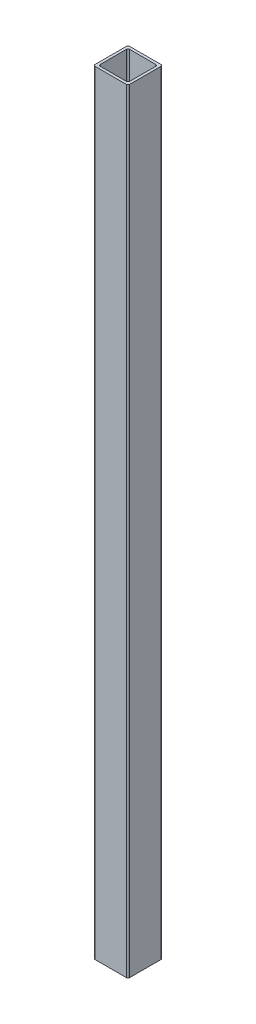
SolidWorks part; units mm, degrees
material "Hexcel AS4C (3000 Filaments)"
ref_plane "Front Plane" through (0, 0, 0) normal (0, 0, 1) x (1, 0, 0)
ref_plane "Top Plane" through (0, 0, 0) normal (0, 1, 0) x (1, 0, 0)
ref_plane "Right Plane" through (0, 0, 0) normal (1, 0, 0) x (0, 0, -1)
sketch "Sketch1" plane through (0, 0, 0) normal (0, 1, 0) x (1, 0, 0)
  line L1 (-9, -10) -> (9, -10)
  line L2 (-10, -9) -> (-10, 9)
  line L3 (-9, 10) -> (9, 10)
  line L4 (10, -9) -> (10, 9)
  line L5 (-10, -10) -> (10, 10) construction
  line L6 (-10, 10) -> (10, -10) construction
  line L7 (-7.5, -8.5) -> (7.5, -8.5)
  line L8 (-8.5, -7.5) -> (-8.5, 7.5)
  line L9 (-7.5, 8.5) -> (7.5, 8.5)
  line L10 (8.5, -7.5) -> (8.5, 7.5)
  line L11 (-8.5, -8.5) -> (8.5, 8.5) construction
  line L12 (-8.5, 8.5) -> (8.5, -8.5) construction
  arc A0 (-9, -10) -> (-10, -9) centre (-9, -9) cw
  arc A1 (9, 10) -> (10, 9) centre (9, 9) cw
  arc A2 (9, -10) -> (10, -9) centre (9, -9) ccw
  arc A3 (-10, 9) -> (-9, 10) centre (-9, 9) cw
  arc A4 (-7.5, -8.5) -> (-8.5, -7.5) centre (-7.5, -7.5) cw
  arc A5 (7.5, -8.5) -> (8.5, -7.5) centre (7.5, -7.5) ccw
  arc A6 (7.5, 8.5) -> (8.5, 7.5) centre (7.5, 7.5) cw
  arc A7 (-8.5, 7.5) -> (-7.5, 8.5) centre (-7.5, 7.5) cw
  point P0 (0, 0)
  point P18 (0, 0)
  dimension "D3" = 1
  dimension "D6" = 1
  dimension "D7" = 1
  dimension "D8" = 1
  dimension "D9" = 1
  dimension "D1" = 20
  dimension "D2" = 20
  dimension "D4" = 17
  dimension "D5" = 17
extrude "Boss-Extrude1" add sketch "Sketch1" along normal blind 447.59
